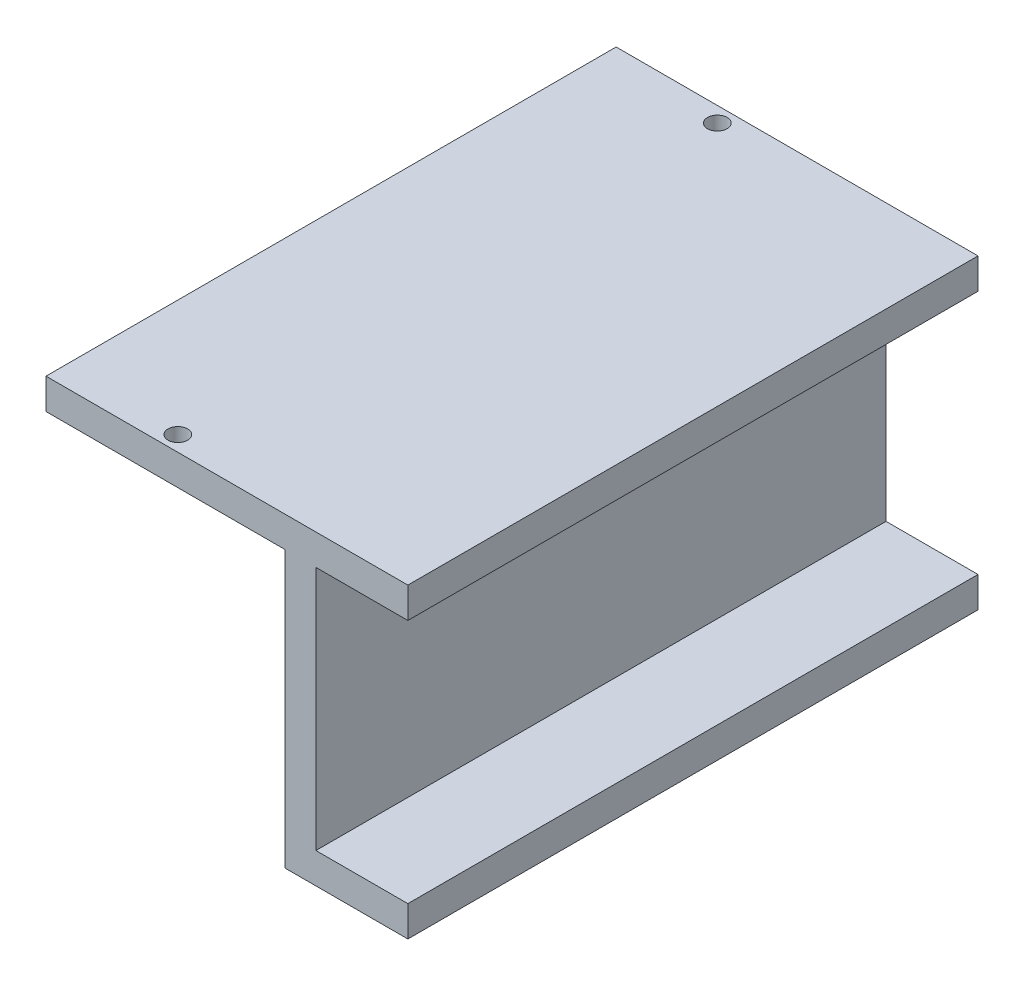
SolidWorks part; units mm, degrees
ref_plane "Plan de face" through (0, 0, 0) normal (0, 0, 1) x (1, 0, 0)
ref_plane "Plan de dessus" through (0, 0, 0) normal (0, 1, 0) x (1, 0, 0)
ref_plane "Plan de droite" through (0, 0, 0) normal (1, 0, 0) x (0, 0, -1)
sketch "Esquisse1" plane through (0, 0, 0) normal (0, 0, 1) x (1, 0, 0)
  line L1 (-20, -469.4099) -> (-59.0251, -469.4099)
  line L2 (-59.0251, -469.4099) -> (-59.0251, -464.4099)
  line L3 (-107.5251, -464.4099) -> (-20.3251, -464.4099) construction
  line L4 (-59.0251, -464.4099) -> (0, -464.4099)
  line L13 (-20, -514.4099) -> (0, -514.4099)
  line L14 (-20, -469.4099) -> (-20, -514.4099)
  line L15 (-15, -469.4099) -> (0, -469.4099)
  line L16 (-15, -509.4099) -> (0, -509.4099)
  line L17 (-15, -509.4099) -> (-15, -469.4099)
  line L18 (0, -514.4099) -> (0, -509.4099)
  line L19 (0, -469.4099) -> (0, -464.4099)
  dimension "D1" = 59.0251
extrude "Boss.-Extru.1" add sketch "Esquisse1" against normal up to surface (93 mm away)
sketch "Esquisse2" plane through (0, -464.4099, 0) normal (0, 1, 0) x (1, 0, 0)
  circle A0 centre (-40.0251, 90.5) radius 1.6 construction
  circle A1 centre (-40.0251, 2.5) radius 1.6 construction
  circle A2 centre (-40.0251, 90.5) radius 1.6
  circle A3 centre (-40.0251, 2.5) radius 1.6
extrude "Enlèv. mat.-Extru.1" cut sketch "Esquisse2" against normal through all
